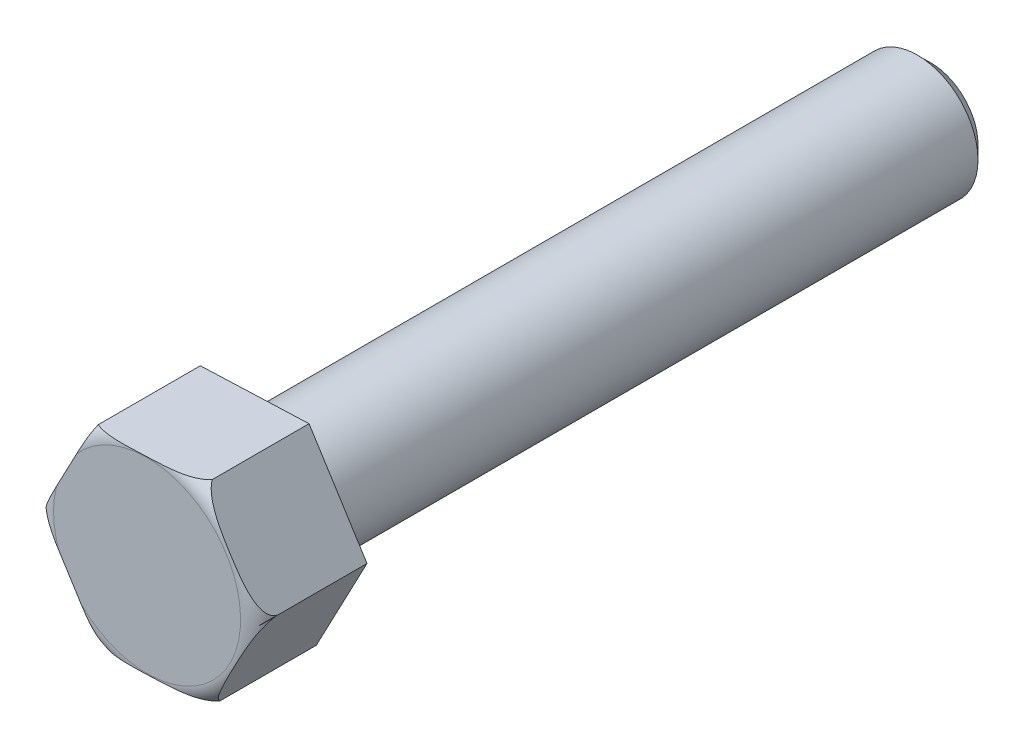
SolidWorks part; units mm, degrees
ref_plane "Front Plane" through (0, 0, 0) normal (0, 0, 1) x (1, 0, 0)
ref_plane "Top Plane" through (0, 0, 0) normal (0, 1, 0) x (1, 0, 0)
ref_plane "Right Plane" through (0, 0, 0) normal (1, 0, 0) x (0, 0, -1)
sketch "Sketch1" plane through (0, 0, 0) normal (0, 0, 1) x (1, 0, 0)
  circle A0 centre (0, 0) radius 2.25
  dimension "D1" = 4.5
extrude "Boss-Extrude1" add sketch "Sketch1" along normal blind 25
sketch "Sketch2" plane through (0, 0, 25) normal (0, 0, 1) x (1, 0, 0)
  line L1 (1.8862, 3.5777) -> (-2.1553, 3.4223)
  line L2 (-2.1553, 3.4223) -> (-4.0415, -0.1554)
  line L3 (-4.0415, -0.1554) -> (-1.8862, -3.5777)
  line L4 (-1.8862, -3.5777) -> (2.1553, -3.4223)
  line L5 (2.1553, -3.4223) -> (4.0415, 0.1554)
  line L6 (4.0415, 0.1554) -> (1.8862, 3.5777)
  circle A0 centre (0, 0) radius 3.5026 construction
  point P1 (-0.1345, 3.5)
  point P10 (0.1345, -3.5)
  dimension "D1" = 7
extrude "Boss-Extrude2" add sketch "Sketch2" along normal blind 4
sketch "Sketch4" plane through (0, 0, 0) normal (0, 1, 0) x (1, 0, 0)
  line L0 (4.0415, -28.3) -> (4.0415, -29)
  line L1 (4.0415, -29) -> (4.0415, -25) construction
  line L2 (4.0415, -29) -> (3.3415, -29)
  line L3 (4.0415, -29) -> (1.8862, -29) construction
  line L4 (-0.1345, -29) -> (-0.1345, -26.1836) construction
  line L5 (1.8862, -29) -> (-2.1553, -29) construction
  arc A0 (4.0415, -28.3) -> (3.3415, -29) centre (3.3415, -28.3) cw
  dimension "D1" = 0.7
revolve "Cut-Revolve1" cut sketch "Sketch4" angle 360 about L4
chamfer "Chamfer1" distance 0.5 angle 45 1 edges at (2.25, 0, 0)
